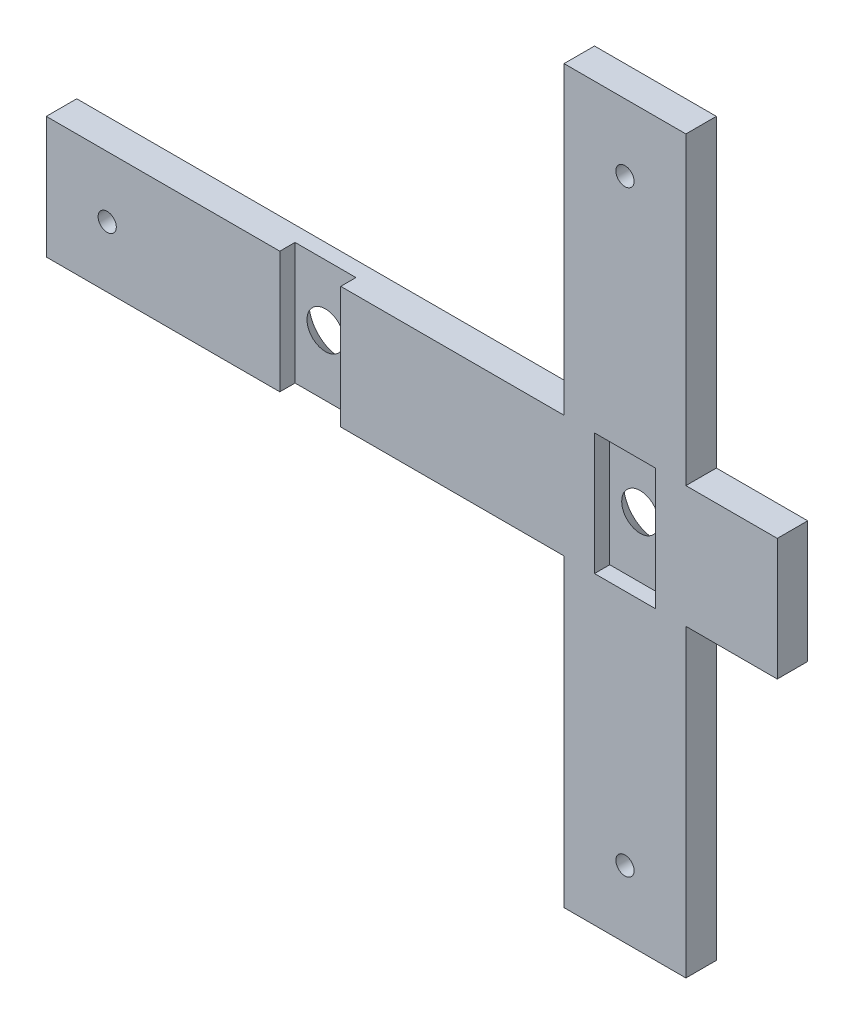
SolidWorks part; units mm, degrees
material "Brass"
ref_plane "Front Plane" through (0, 0, 0) normal (0, 0, 1) x (1, 0, 0)
ref_plane "Top Plane" through (0, 0, 0) normal (0, 1, 0) x (1, 0, 0)
ref_plane "Right Plane" through (0, 0, 0) normal (1, 0, 0) x (0, 0, -1)
sketch "Sketch1" plane through (0, 0, 0) normal (0, 0, 1) x (1, 0, 0)
  line L0 (-76.2, 76.2) -> (76.2, -76.2) construction
  line L1 (-76.2, 76.2) -> (76.2, 76.2)
  line L2 (-76.2, 76.2) -> (-76.2, -76.2)
  line L3 (-76.2, -76.2) -> (76.2, -76.2)
  line L4 (76.2, 76.2) -> (76.2, -76.2)
  dimension "D1" = 152.4
  dimension "D2" = 152.4
extrude "Extrude1" add sketch "Sketch1" along normal blind 6.35
sketch "Sketch2" plane through (0, 0, 6.35) normal (0, 0, 1) x (1, 0, 0)
  line L0 (0, -1000) -> (0, 49000) construction
  line L1 (-1000, 0) -> (49000, 0) construction
  line L2 (-132.7586, -39.9865) -> (29.8222, 53.8796) construction
  line L3 (-974.9255, 526.2118) -> (42254.3563, -24432.2257) construction
sketch "Sketch3" plane through (0, 0, 6.35) normal (0, 0, 1) x (1, 0, 0)
  line L0 (57.15, 76.2) -> (57.15, 12.7)
  line L1 (-76.2, 76.2) -> (-76.2, -76.2) construction
  line L2 (76.2, 76.2) -> (-76.2, 76.2) construction
  line L4 (57.15, 12.7) -> (76.2, 12.7)
  line L5 (57.15, -12.7) -> (57.15, -76.2)
  line L6 (-76.2, -76.2) -> (76.2, -76.2) construction
  line L7 (76.2, -76.2) -> (76.2, 76.2) construction
  line L8 (76.2, 12.7) -> (76.2, -12.7)
  line L9 (57.15, -76.2) -> (31.75, -76.2)
  line L10 (31.75, -76.2) -> (31.75, -12.7)
  line L12 (31.75, -12.7) -> (-76.2, -12.7)
  line L13 (-76.2, 12.7) -> (31.75, 12.7)
  line L14 (31.75, 12.7) -> (31.75, 76.2)
  line L15 (-76.2, -12.7) -> (-76.2, 12.7)
  line L16 (-1000, 0) -> (49000, 0) construction
  line L17 (44.45, -977.9291) -> (44.45, 49022.0709) construction
  line L18 (31.75, 76.2) -> (57.15, 76.2)
  line L20 (76.2, -12.7) -> (57.15, -12.7)
  dimension "D1" = 12.7
  dimension "D2" = 31.75
  dimension "D3" = 12.7
  dimension "D4" = 12.7
  dimension "D5" = 12.7
  dimension "D6" = 12.7
extrude "Extrude3" cut sketch "Sketch3" against normal through all flip side to cut
hole_wizard "CSK for 1/4 Flat Head Socket Cap Screw2" positions "Sketch10" profile "Sketch11" countersink size "1/4" standard "Ansi Inch" end condition through all
sketch "Sketch10" plane through (22.3322, 5.3613, 0) normal (0, 0, -1) x (1, 0, 0)
  line L1 (22.1178, 5.3613) -> (22.1178, 15.989) construction
  point P0 (-43.4929, 5.3613)
sketch "Sketch11" plane through (-21.1607, 0, 0) normal (1, 0, 0) x (0, 1, 0)
  line L0 (0, 0) -> (0, 6.35)
  line L1 (0, 6.35) -> (3.3782, 6.35)
  line L2 (3.3782, 6.35) -> (3.3782, 3.7284)
  line L3 (3.3782, 3.7284) -> (6.6192, 0)
  line L5 (6.6192, 0) -> (0, 0)
  line L6 (-3.3782, 3.7284) -> (-6.6192, 0) construction
  line L11 (0, -6.35) -> (0, 107.95) construction
  dimension "Thru Hole Dia." = 6.7564
  dimension "Thru Hole Depth" = 6.35
  dimension "Near C'Sink Dia." = 13.2385
  dimension "Near C'Sink Angle" = 82
hole_wizard "CSK for 1/4 Flat Head Socket Cap Screw3" positions "Sketch12" profile "Sketch13" countersink size "1/4" standard "Ansi Inch" end condition through all
sketch "Sketch12" plane through (22.3322, 5.3613, 0) normal (0, 0, -1) x (1, 0, 0)
  point P0 (22.1178, 5.3613)
sketch "Sketch13" plane through (44.45, 0, 0) normal (1, 0, 0) x (0, 1, 0)
  line L0 (0, 0) -> (0, 6.35)
  line L1 (0, 6.35) -> (3.3782, 6.35)
  line L2 (3.3782, 6.35) -> (3.3782, 3.7284)
  line L3 (3.3782, 3.7284) -> (6.6192, 0)
  line L5 (6.6192, 0) -> (0, 0)
  line L6 (-3.3782, 3.7284) -> (-6.6192, 0) construction
  line L11 (0, -6.35) -> (0, 107.95) construction
  dimension "Thru Hole Dia." = 6.7564
  dimension "Thru Hole Depth" = 6.35
  dimension "Near C'Sink Dia." = 13.2385
  dimension "Near C'Sink Angle" = 82
hole_wizard "#10-24 Tapped Hole2" positions "3DSketch2" profile "Sketch15" tap size "#10-24" standard "Ansi Inch"
sketch3d "3DSketch2"
  line L0 (57.15, 12.7, 0) -> (57.15, 76.2, 0) construction
  line L1 (57.15, 76.2, 0) -> (31.75, 76.2, 0) construction
  line L2 (31.75, -76.2, 0) -> (57.15, -76.2, 0) construction
  line L3 (31.75, -12.7, 0) -> (31.75, -76.2, 0) construction
  line L4 (-76.2, -12.7, 0) -> (31.75, -12.7, 0) construction
  line L5 (-76.2, 12.7, 0) -> (-76.2, -12.7, 0) construction
  point P0 (-63.5, 0, 0)
  point P2 (44.45, 62.23, 0)
  point P4 (44.45, -62.23, 0)
  dimension "D1" = 12.7
  dimension "D2" = 13.97
  dimension "D3" = 13.97
  dimension "D4" = 12.7
  dimension "D5" = 12.7
  dimension "D6" = 12.7
sketch "Sketch15" plane through (-63.5, 0, 0) normal (1, 0, 0) x (0, 1, 0)
  line L0 (0, 0) -> (0, 16.1268)
  line L1 (0, 16.1268) -> (1.8986, 14.986)
  line L2 (1.8986, 14.986) -> (1.8986, 0)
  line L5 (1.8986, 0) -> (0, 0)
  line L10 (0, 16.1268) -> (-1.8986, 14.986) construction
  line L11 (0, -6.35) -> (0, 107.95) construction
  dimension "Tap Drill Dia." = 3.7973
  dimension "Tap Drill Depth" = 14.986
  dimension "Drill Angle" = 118
cosmetic thread "Hole Thread6" parameters "D1"=6.35, "D2"=4.826
cosmetic thread "Hole Thread7" parameters "D1"=6.35, "D2"=4.826
cosmetic thread "Hole Thread8" parameters "D1"=6.35, "D2"=4.826
sketch "Sketch18" plane through (0, 0, 6.35) normal (0, 0, 1) x (1, 0, 0)
  line L0 (-21.1607, 0) -> (-21.1607, 14.3495) construction
  line L1 (-1020.1869, 0) -> (48979.8131, 0) construction
  line L2 (-27.5107, -1000) -> (-27.5107, 49000) construction
  line L3 (-14.8107, -1001.2593) -> (-14.8107, 48998.7407) construction
  line L4 (-27.5107, 12.7) -> (-27.5107, -12.7026)
  line L5 (31.75, 12.7) -> (-76.2, 12.7) construction
  line L6 (-27.5107, -12.7026) -> (-14.8107, -12.7)
  line L7 (-76.2, -12.7) -> (31.75, -12.7) construction
  line L8 (-14.8107, -12.7) -> (-14.8107, 12.7)
  line L9 (-14.8107, 12.7) -> (-27.5107, 12.7)
  dimension "D1" = 6.35
  dimension "D2" = 6.35
extrude "Extrude4" cut sketch "Sketch18" against normal blind 3.175
sketch "Sketch20" plane through (0, 0, 6.35) normal (0, 0, 1) x (1, 0, 0)
  line L0 (44.45, 0) -> (44.45, 10.0599) construction
  line L1 (-954.6549, 0) -> (49045.3451, 0) construction
  line L2 (38.1, -997.6019) -> (38.1, 49002.3981) construction
  line L3 (50.8, -998.3022) -> (50.8, 49001.6978) construction
  line L4 (-958.3764, 12.7) -> (49041.6236, 12.7) construction
  line L5 (-954.5455, -12.7) -> (49045.4545, -12.7) construction
  line L6 (38.1, 12.7) -> (38.1, -12.7)
  line L7 (38.1, -12.7) -> (50.8, -12.7)
  line L8 (50.8, -12.7) -> (50.8, 12.7)
  line L9 (50.8, 12.7) -> (38.1, 12.7)
  dimension "D1" = 6.35
  dimension "D2" = 6.35
  dimension "D3" = 12.7
  dimension "D4" = 12.7
extrude "Extrude5" cut sketch "Sketch20" against normal blind 3.175
